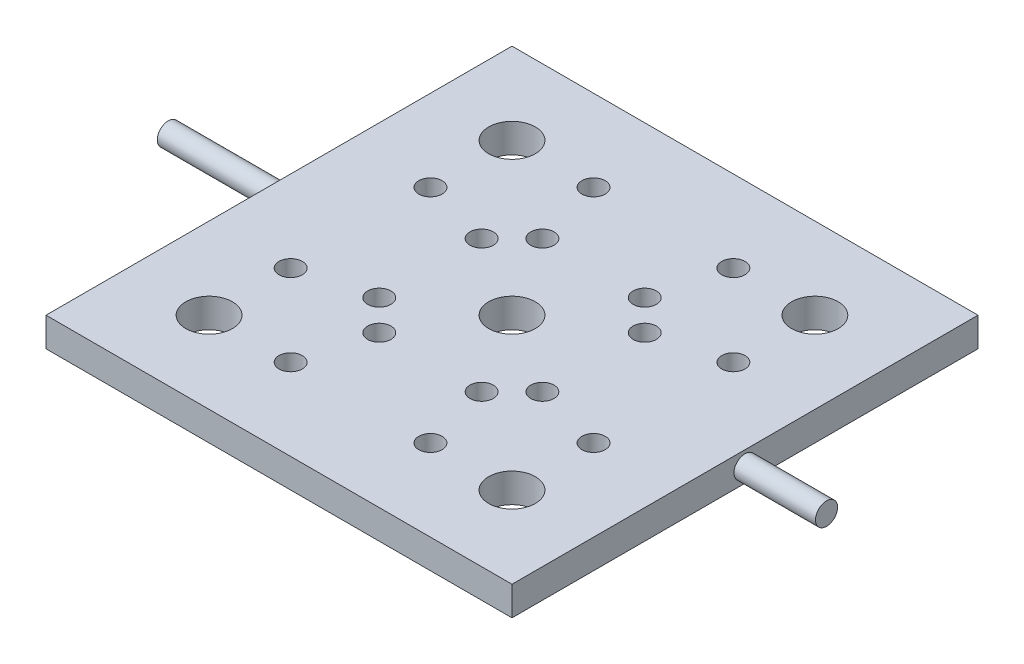
SolidWorks part; units mm, degrees
ref_plane "Front Plane" through (0, 0, 0) normal (0, 0, 1) x (1, 0, 0)
ref_plane "Top Plane" through (0, 0, 0) normal (0, 1, 0) x (1, 0, 0)
ref_plane "Right Plane" through (0, 0, 0) normal (1, 0, 0) x (0, 0, -1)
sketch "Sketch1" plane through (0, 0, 0) normal (0, 1, 0) x (1, 0, 0)
  line L1 (-25.4, -25.4) -> (25.4, -25.4)
  line L2 (-25.4, -25.4) -> (-25.4, 25.4)
  line L3 (-25.4, 25.4) -> (25.4, 25.4)
  line L4 (25.4, -25.4) -> (25.4, 25.4)
  line L5 (-25.4, -25.4) -> (25.4, 25.4) construction
  line L6 (-25.4, 25.4) -> (25.4, -25.4) construction
  point P0 (0, 0)
  dimension "D1" = 50.8
extrude "Boss-Extrude1" add sketch "Sketch1" along normal mid plane 3.175
sketch "Sketch3" plane through (25.4, 0, 0) normal (1, 0, 0) x (0, 0, -1)
  circle A0 centre (0, 0) radius 1.2065
  dimension "D1" = 2.413
extrude "Boss-Extrude2" add sketch "Sketch3" along normal blind 8.89
sketch "Sketch4" plane through (0, 1.5875, 0) normal (0, 1, 0) x (1, 0, 0)
  line L0 (25.4, 25.4) -> (-25.4, 25.4) construction
  line L1 (-25.4, 25.4) -> (-25.4, -25.4) construction
  line L2 (25.4, -25.4) -> (25.4, 25.4) construction
  line L3 (25.4, -25.4) -> (25.4, 25.4) construction
  line L4 (-25.4, -25.4) -> (25.4, -25.4) construction
  line L5 (-25.4, 25.4) -> (-25.4, -25.4) construction
  line L6 (-25.4, 0) -> (25.4, 0) construction
  line L7 (0, 25.4) -> (0, -25.4) construction
  line L8 (-7.62, 16.51) -> (-7.62, 0) construction
  line L9 (-7.62, 16.51) -> (5.5782, 8.89) construction
  line L10 (7.62, 16.51) -> (7.62, 0) construction
  line L11 (-5.5782, 8.89) -> (7.62, 16.51) construction
  line L12 (-25.4, 25.4) -> (-25.4, -25.4) construction
  line L14 (25.4, -25.4) -> (25.4, 25.4) construction
  circle A0 centre (0, 0) radius 2.54
  circle A1 centre (-16.51, 16.51) radius 2.54
  circle A2 centre (16.51, 16.51) radius 2.54
  circle A3 centre (16.51, -16.51) radius 2.54
  circle A4 centre (-16.51, -16.51) radius 2.54
  circle A5 centre (-16.51, 7.62) radius 1.27
  circle A6 centre (-7.62, 16.51) radius 1.27
  circle A7 centre (7.62, 16.51) radius 1.27
  circle A14 centre (-16.51, -7.62) radius 1.27
  circle A17 centre (7.62, -16.51) radius 1.27
  circle A18 centre (-7.62, -16.51) radius 1.27
  circle A19 centre (16.51, -7.62) radius 1.27
  circle A20 centre (16.51, 7.62) radius 1.27
  circle A21 centre (5.5782, 8.89) radius 1.27
  circle A22 centre (-5.5782, 8.89) radius 1.27
  circle A23 centre (8.89, -5.5782) radius 1.27
  circle A24 centre (8.89, 5.5782) radius 1.27
  circle A25 centre (-5.5782, -8.89) radius 1.27
  circle A26 centre (5.5782, -8.89) radius 1.27
  circle A27 centre (-8.89, 5.5782) radius 1.27
  circle A28 centre (-8.89, -5.5782) radius 1.27
  point P66 (0, 0)
  point P68 (-25.4, 0)
  point P71 (25.4, 0)
  dimension "D1" = 5.08
  dimension "D2" = 2.54
  dimension "D3" = 8.89
  dimension "D4" = 8.89
  dimension "D5" = 8.89
  dimension "D6" = 8.89
  dimension "D7" = 8.89
  dimension "D8" = 8.89
  dimension "D9" = 8.89
  dimension "D10" = 8.89
  dimension "D11" = 15.24
  dimension "D12" = 15.24
  dimension "D13" = 15.24
  dimension "D14" = 8.89
  dimension "D15" = 8.89
  dimension "D16" = 60
  dimension "D17" = 15.24
  dimension "D18" = 60
  dimension "D19" = 4
extrude "Cut-Extrude1" cut sketch "Sketch4" against normal through all
sketch "Sketch5" plane through (-25.4, 0, 0) normal (-1, 0, 0) x (0, 0, 1)
  circle A0 centre (0, 0) radius 1.2065
  dimension "D1" = 2.413
extrude "Boss-Extrude3" add sketch "Sketch5" along normal blind 12.065
